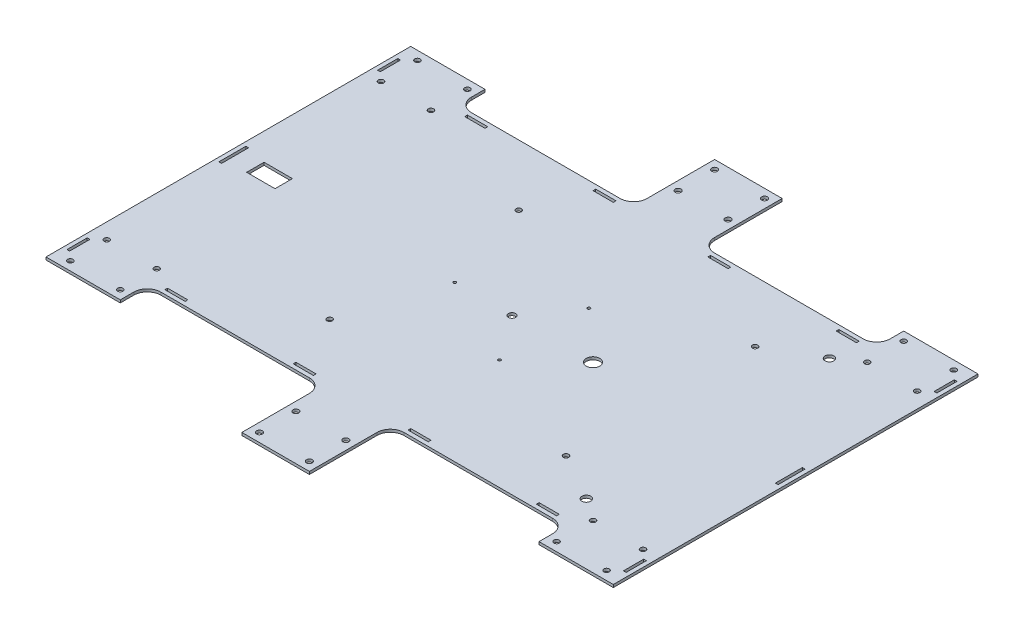
SolidWorks part; units mm, degrees
material "6061 合金"
ref_plane "前视基准面" through (0, 0, 0) normal (0, 0, 1) x (1, 0, 0)
ref_plane "上视基准面" through (0, 0, 0) normal (0, 1, 0) x (1, 0, 0)
ref_plane "右视基准面" through (0, 0, 0) normal (1, 0, 0) x (0, 0, -1)
sketch "草图1" plane through (0, 0, 0) normal (0, 1, 0) x (1, 0, 0)
  line L0 (0, -137.5) -> (0, 137.5) construction
  line L1 (-210, -135) -> (-25, -135)
  line L2 (-210, -135) -> (-210, 135)
  line L3 (-210, 135) -> (-25, 135)
  line L4 (210, -135) -> (210, 135)
  line L5 (-210, -135) -> (210, 135) construction
  line L6 (-210, 135) -> (210, -135) construction
  line L7 (210, 0) -> (-210, 0) construction
  line L8 (-155, 135) -> (-155, 95) construction
  line L9 (-155, 95) -> (-205, 95) construction
  line L10 (-205, 135) -> (-205, 95) construction
  line L11 (-155, -95) -> (-205, -95) construction
  line L12 (-205, -135) -> (-205, -95) construction
  line L13 (-155, -135) -> (-155, -95) construction
  line L14 (205, -135) -> (205, -95) construction
  line L15 (155, -95) -> (205, -95) construction
  line L16 (155, -135) -> (155, -95) construction
  line L17 (155, 135) -> (155, 95) construction
  line L18 (205, 135) -> (205, 95) construction
  line L19 (155, 95) -> (205, 95) construction
  line L20 (0, 137.5) -> (0, 155) construction
  line L21 (25, -175) -> (25, -135)
  line L22 (-25, 175) -> (25, 175)
  line L23 (-25, 175) -> (-25, 135)
  line L24 (25, -135) -> (210, -135)
  line L25 (25, 175) -> (25, 135)
  line L26 (-25, 175) -> (25, 135) construction
  line L27 (-25, 135) -> (25, 175) construction
  line L28 (-25, -175) -> (25, -175)
  line L29 (-25, -175) -> (-25, -135)
  line L30 (25, 135) -> (210, 135)
  line L31 (-180, 95) -> (-180, 135) construction
  circle A0 centre (198.5, 128.5) radius 2
  circle A1 centre (198.5, 101.5) radius 2
  circle A2 centre (161.5, 101.5) radius 2
  circle A3 centre (161.5, 128.5) radius 2
  circle A4 centre (198.5, -128.5) radius 2
  circle A5 centre (198.5, -101.5) radius 2
  circle A6 centre (161.5, -101.5) radius 2
  circle A7 centre (161.5, -128.5) radius 2
  circle A8 centre (-161.5, 128.5) radius 2
  circle A9 centre (-161.5, 101.5) radius 2
  circle A10 centre (-198.5, 101.5) radius 2
  circle A11 centre (-198.5, 128.5) radius 2
  circle A12 centre (-161.5, -128.5) radius 2
  circle A13 centre (-161.5, -101.5) radius 2
  circle A14 centre (-198.5, -101.5) radius 2
  circle A15 centre (-198.5, -128.5) radius 2
  circle A16 centre (18.5, 168.5) radius 2.15
  circle A17 centre (-18.5, 168.5) radius 2.15
  circle A18 centre (-18.5, 141.5) radius 2.15
  circle A19 centre (18.5, 141.5) radius 2.15
  circle A20 centre (-18.5, -141.5) radius 2.15
  circle A21 centre (18.5, -141.5) radius 2.15
  circle A22 centre (18.5, -168.5) radius 2.15
  circle A23 centre (-18.5, -168.5) radius 2.15
  point P0 (0, 0)
  point P17 (0, 0)
  point P20 (0, 0)
  dimension "D3" = 4
  dimension "D4" = 6.5
  dimension "D5" = 6.5
  dimension "D7" = 27
  dimension "D17" = 4.3
  dimension "D9" = 6.5
  dimension "D1" = 420
  dimension "D2" = 270
  dimension "D6" = 37
  dimension "D8" = 6.5
  dimension "D10" = 37
  dimension "D11" = 27
  dimension "D12" = 180
  dimension "D13" = 50
  dimension "D14" = 17.5
  dimension "D15" = 50
  dimension "D16" = 40
  dimension "D18" = 6.5
  dimension "D19" = 6.5
  dimension "D20" = 6.5
  dimension "D21" = 6.5
  dimension "D22" = 27
  dimension "D23" = 27
  dimension "D24" = 37
  dimension "D25" = 6.5
  dimension "D26" = 40
extrude "凸台-拉伸1" add sketch "草图1" along normal blind 2
sketch "草图2" plane through (0, 2, 0) normal (0, 1, 0) x (1, 0, 0)
  line L1 (-25, 135) -> (-155, 135)
  line L2 (-25, 135) -> (-25, 125)
  line L3 (-35, 115) -> (-145, 115)
  line L4 (-155, 135) -> (-155, 125)
  circle A0 centre (-161.5, 128.5) radius 2 construction
  arc A1 (-145, 115) -> (-155, 125) centre (-145, 125) cw
  arc A2 (-25, 125) -> (-35, 115) centre (-35, 125) cw
  point P11 (-25, 115)
  dimension "D1" = 6.5
  dimension "D3" = 10
  dimension "D4" = 10
  dimension "D2" = 20
extrude "切除-拉伸1" cut sketch "草图2" against normal through all
mirror "镜向1" about plane through (0, 0, 0) normal (0, 0, 1) of "切除-拉伸1"
mirror "镜向2" about plane through (0, 0, 0) normal (1, 0, 0) of "镜向1", "切除-拉伸1"
sketch "草图3" plane through (0, 2, 0) normal (0, 1, 0) x (1, 0, 0)
  line L0 (-210, 135) -> (-210, -135) construction
  line L1 (-205, 122.5) -> (-207, 122.5)
  line L2 (-205, 122.5) -> (-205, 107.5)
  line L3 (-205, 107.5) -> (-207, 107.5)
  line L4 (-207, 122.5) -> (-207, 107.5)
  line L5 (-205, 122.5) -> (-207, 107.5) construction
  line L6 (-205, 107.5) -> (-207, 122.5) construction
  line L7 (-155, 135) -> (-210, 135) construction
  line L8 (0, -175) -> (0, 175) construction
  line L9 (-205, 10) -> (-207, 10)
  line L10 (-205, 10) -> (-205, -10)
  line L11 (-205, -10) -> (-207, -10)
  line L12 (-207, 10) -> (-207, -10)
  line L13 (-205, 10) -> (-207, -10) construction
  line L14 (-205, -10) -> (-207, 10) construction
  line L15 (25, 175) -> (-25, 175) construction
  line L16 (-210, 0) -> (210, 0) construction
  line L17 (210, -135) -> (210, 135) construction
  line L18 (-210, -135) -> (-155, -135) construction
  line L19 (-205, -107.5) -> (-207, -107.5)
  line L20 (-205, -107.5) -> (-205, -122.5)
  line L21 (-205, -122.5) -> (-207, -122.5)
  line L22 (-207, -107.5) -> (-207, -122.5)
  line L23 (-205, -107.5) -> (-207, -122.5) construction
  line L24 (-205, -122.5) -> (-207, -107.5) construction
  line L25 (205, -107.5) -> (207, -107.5)
  line L26 (207, -107.5) -> (207, -122.5)
  line L27 (205, -122.5) -> (207, -122.5)
  line L28 (205, -107.5) -> (205, -122.5)
  line L29 (205, -10) -> (207, -10)
  line L30 (207, 10) -> (207, -10)
  line L31 (205, 10) -> (207, 10)
  line L32 (205, 10) -> (205, -10)
  line L33 (205, 107.5) -> (207, 107.5)
  line L34 (207, 122.5) -> (207, 107.5)
  line L35 (205, 122.5) -> (207, 122.5)
  line L36 (205, 122.5) -> (205, 107.5)
  line L37 (-155, 135) -> (-155, 125) construction
  line L38 (-145, 110) -> (-130, 110)
  line L39 (-145, 110) -> (-145, 112)
  line L40 (-145, 112) -> (-130, 112)
  line L41 (-130, 110) -> (-130, 112)
  line L42 (-145, 110) -> (-130, 112) construction
  line L43 (-145, 112) -> (-130, 110) construction
  line L45 (-145, 115) -> (-35, 115) construction
  line L46 (-25, 175) -> (-25, 125) construction
  line L47 (-50, 110) -> (-35, 110)
  line L48 (-50, 110) -> (-50, 112)
  line L49 (-50, 112) -> (-35, 112)
  line L50 (-35, 110) -> (-35, 112)
  line L51 (-50, 110) -> (-35, 112) construction
  line L52 (-50, 112) -> (-35, 110) construction
  line L53 (35, 110) -> (35, 112)
  line L54 (50, 112) -> (35, 112)
  line L55 (50, 110) -> (50, 112)
  line L56 (50, 110) -> (35, 110)
  line L57 (145, 110) -> (145, 112)
  line L58 (130, 110) -> (130, 112)
  line L59 (145, 112) -> (130, 112)
  line L60 (145, 110) -> (130, 110)
  line L61 (145, -110) -> (145, -112)
  line L62 (145, -112) -> (130, -112)
  line L63 (130, -110) -> (130, -112)
  line L64 (145, -110) -> (130, -110)
  line L65 (50, -110) -> (50, -112)
  line L66 (50, -112) -> (35, -112)
  line L67 (35, -110) -> (35, -112)
  line L68 (50, -110) -> (35, -110)
  line L69 (-50, -110) -> (-50, -112)
  line L70 (-50, -112) -> (-35, -112)
  line L71 (-35, -110) -> (-35, -112)
  line L72 (-50, -110) -> (-35, -110)
  line L73 (-130, -110) -> (-130, -112)
  line L74 (-145, -112) -> (-130, -112)
  line L75 (-145, -110) -> (-145, -112)
  line L76 (-145, -110) -> (-130, -110)
  point P0 (-206, 115)
  point P9 (-206, 0)
  point P14 (-206, -115)
  point P20 (0, 0)
  point P26 (0, 0)
  point P45 (-137.5, 111)
  point P53 (-42.5, 111)
  dimension "D1" = 15
  dimension "D2" = 2
  dimension "D3" = 3
  dimension "D4" = 20
  dimension "D5" = 20
  dimension "D6" = 2
  dimension "D7" = 3
  dimension "D8" = 15
  dimension "D9" = 2
  dimension "D10" = 20
  dimension "D11" = 3
  dimension "D12" = 15
  dimension "D13" = 2
  dimension "D14" = 10
  dimension "D15" = 3
  dimension "D16" = 15
  dimension "D17" = 2
  dimension "D18" = 3
  dimension "D19" = 10
extrude "切除-拉伸2" cut sketch "草图3" against normal through all
sketch "草图4" plane through (0, 0, 0) normal (0, -1, 0) x (1, 0, 0)
  line L0 (-205, 10) -> (-205, -10) construction
  line L1 (-190, 6.45) -> (-169, 6.45)
  line L2 (-190, 6.45) -> (-190, -6.45)
  line L3 (-190, -6.45) -> (-169, -6.45)
  line L4 (-169, 6.45) -> (-169, -6.45)
  line L5 (-190, 6.45) -> (-169, -6.45) construction
  line L6 (-190, -6.45) -> (-169, 6.45) construction
  line L7 (-42.4, 0) -> (23.8543, 33.1) construction
  line L8 (-42.4, 0) -> (23.8543, -33.1) construction
  line L9 (23.8543, 33.1) -> (23.8543, -33.1) construction
  line L10 (-210, -135) -> (-210, 135) construction
  line L11 (145, -115) -> (35, -115) construction
  line L12 (210, 135) -> (210, -135) construction
  line L13 (145, 115) -> (35, 115) construction
  circle A0 centre (0, 0) radius 2.6
  circle A1 centre (23.8543, 33.1) radius 1
  circle A2 centre (23.8543, -33.1) radius 1
  circle A3 centre (-42.4, 0) radius 1
  circle A4 centre (-65, 70) radius 2
  circle A5 centre (110, 70) radius 2
  circle A6 centre (-65, -70) radius 2
  circle A7 centre (110, -70) radius 2
  circle A8 centre (145, -90) radius 3.25
  circle A9 centre (145, 90) radius 3.25
  circle A10 centre (60, 0) radius 5
  point P0 (-179.5, 0)
  point P7 (-190, 0)
  point P8 (-205, 0)
  dimension "D4" = 5.2
  dimension "D5" = 40.8
  dimension "D6" = 2
  dimension "D7" = 2
  dimension "D8" = 40.8
  dimension "D9" = 66.2
  dimension "D10" = 2
  dimension "D11" = 42.4
  dimension "D12" = 4
  dimension "D13" = 145
  dimension "D14" = 70
  dimension "D15" = 175
  dimension "D16" = 70
  dimension "D17" = 145
  dimension "D18" = 70
  dimension "D19" = 175
  dimension "D20" = 70
  dimension "D21" = 6.5
  dimension "D22" = 6.5
  dimension "D23" = 25
  dimension "D24" = 65
  dimension "D25" = 65
  dimension "D26" = 25
  dimension "D27" = 10
  dimension "D28" = 60
  dimension "D29" = 115
  dimension "D1" = 12.9
  dimension "D2" = 21
  dimension "D3" = 15
extrude "切除-拉伸3" cut sketch "草图4" against normal through all
